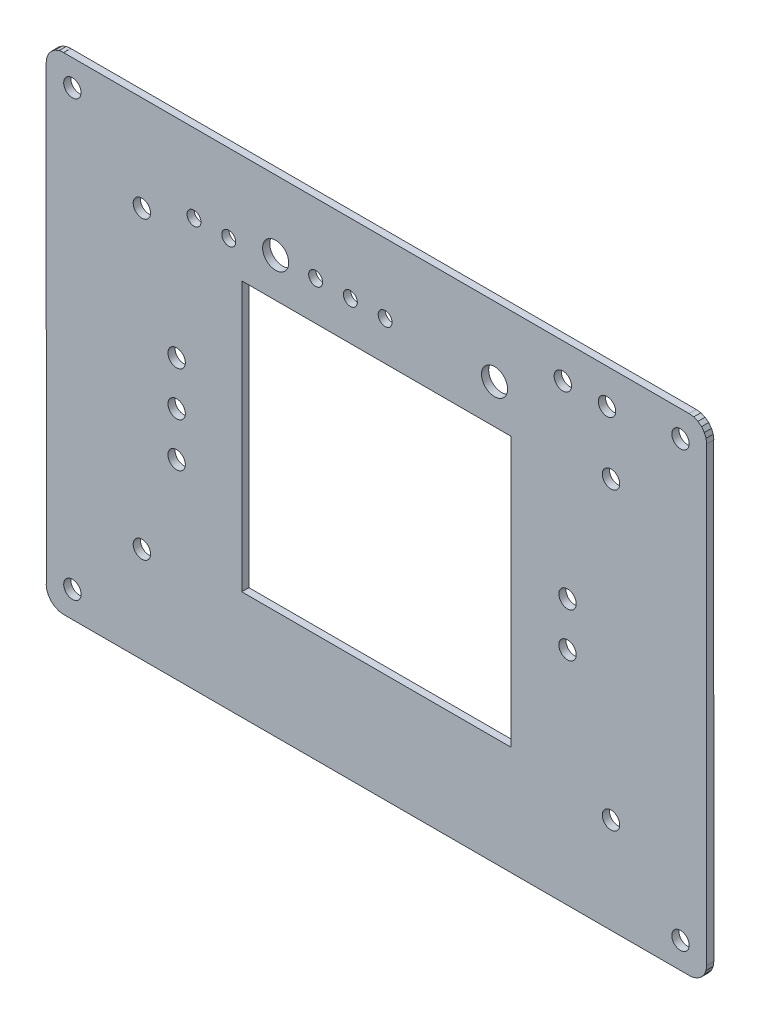
SolidWorks part; units mm, degrees
ref_plane "前视基准面" through (0, 0, 0) normal (0, 0, 1) x (1, 0, 0)
ref_plane "上视基准面" through (0, 0, 0) normal (0, 1, 0) x (1, 0, 0)
ref_plane "右视基准面" through (0, 0, 0) normal (1, 0, 0) x (0, 0, -1)
sketch "草图1" plane through (0, 0, 0) normal (0, 0, 1) x (1, 0, 0)
  line L0 (28.25, 7.75) -> (12.75, 7.75)
  line L1 (12.75, 7.75) -> (12.75, 23.25)
  line L2 (12.75, 23.25) -> (28.25, 23.25)
  line L3 (28.25, 23.25) -> (28.25, 7.75)
  line L4 (1.5257, 2.2389) -> (1.6265, 1.9957)
  line L5 (1.6265, 1.9957) -> (1.7868, 1.7868)
  line L6 (1.7868, 1.7868) -> (1.9957, 1.6265)
  line L7 (1.9957, 1.6265) -> (2.2389, 1.5257)
  line L8 (2.2389, 1.5257) -> (2.5, 1.4914)
  line L9 (2.5, 1.4914) -> (38.5, 1.5)
  line L10 (38.5, 1.5) -> (38.5, 1.4914)
  line L11 (38.5, 1.4914) -> (38.7611, 1.5257)
  line L12 (38.7611, 1.5257) -> (39.0043, 1.6265)
  line L13 (39.0043, 1.6265) -> (39.2132, 1.7868)
  line L14 (39.2132, 1.7868) -> (39.3735, 1.9957)
  line L15 (39.3735, 1.9957) -> (39.4743, 2.2389)
  line L16 (39.4743, 2.2389) -> (39.5086, 2.5)
  line L17 (39.5086, 2.5) -> (39.5, 28.5)
  line L18 (39.5, 28.5) -> (39.5086, 28.5)
  line L19 (39.5086, 28.5) -> (39.4743, 28.7611)
  line L20 (39.4743, 28.7611) -> (39.3735, 29.0043)
  line L21 (39.3735, 29.0043) -> (39.2132, 29.2132)
  line L22 (39.2132, 29.2132) -> (39.0043, 29.3735)
  line L23 (39.0043, 29.3735) -> (38.7611, 29.4743)
  line L24 (38.7611, 29.4743) -> (38.5, 29.5086)
  line L25 (38.5, 29.5086) -> (2.5, 29.5)
  line L26 (2.5, 29.5) -> (2.5, 29.5086)
  line L27 (2.5, 29.5086) -> (2.2389, 29.4743)
  line L28 (2.2389, 29.4743) -> (1.9957, 29.3735)
  line L29 (1.9957, 29.3735) -> (1.7868, 29.2132)
  line L30 (1.7868, 29.2132) -> (1.6265, 29.0043)
  line L31 (1.6265, 29.0043) -> (1.5257, 28.7611)
  line L32 (1.5257, 28.7611) -> (1.4914, 28.5)
  line L33 (1.4914, 28.5) -> (1.5, 2.5)
  line L34 (1.5, 2.5) -> (1.4914, 2.5)
  line L35 (1.4914, 2.5) -> (1.5257, 2.2389)
  circle A0 centre (38, 28) radius 0.5
  circle A1 centre (33.77, 27.5) radius 0.5
  circle A2 centre (31.23, 27.5) radius 0.5
  circle A3 centre (19, 25.5) radius 0.4
  circle A4 centre (17, 25.5) radius 0.4
  circle A5 centre (21, 25.5) radius 0.4
  circle A6 centre (34, 7) radius 0.5
  circle A7 centre (34, 24) radius 0.5
  circle A8 centre (38, 3) radius 0.5
  circle A9 centre (31.5, 16.77) radius 0.5
  circle A10 centre (27.3, 25.5) radius 0.75
  circle A11 centre (31.5, 14.23) radius 0.5
  circle A12 centre (14.7, 25.5) radius 0.75
  circle A13 centre (12, 25) radius 0.4
  circle A14 centre (10, 25) radius 0.4
  circle A15 centre (7, 24) radius 0.5
  circle A16 centre (3, 28) radius 0.5
  circle A17 centre (9, 17.54) radius 0.5
  circle A18 centre (9, 15) radius 0.5
  circle A19 centre (9, 12.46) radius 0.5
  circle A20 centre (7, 7) radius 0.5
  circle A21 centre (3, 3) radius 0.5
extrude "凸台-拉伸1" add sketch "草图1" against normal blind 0.4115
sketch "草图2" plane through (0, 0, 0) normal (0, 0, 1) x (1, 0, 0)
  line L0 (110.3881, 244.5343) -> (547.0548, 244.5343) construction
sketch "草图3" plane through (0, 0, -0.4115) normal (0, 0, -1) x (-1, 0, 0)
  line L0 (67.4227, 237.5971) -> (495.4227, 237.5971) construction
